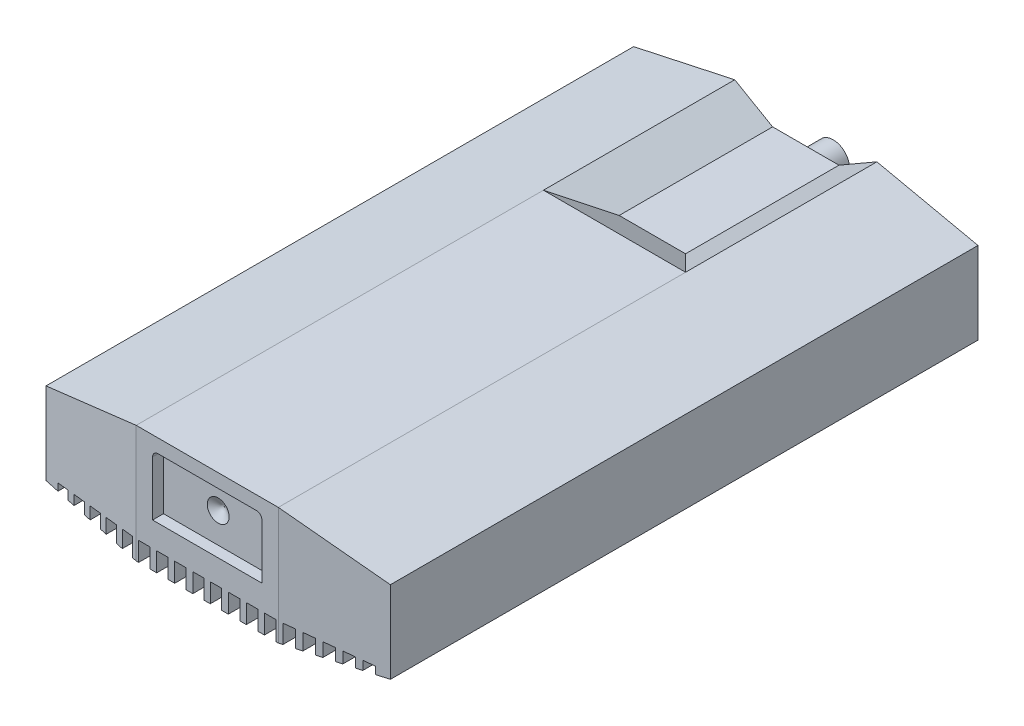
SolidWorks part; units mm, degrees
ref_plane "前视基准面" through (0, 0, 0) normal (0, 0, 1) x (1, 0, 0)
ref_plane "上视基准面" through (0, 0, 0) normal (0, 1, 0) x (1, 0, 0)
ref_plane "右视基准面" through (0, 0, 0) normal (1, 0, 0) x (0, 0, -1)
sketch "草图1" plane through (0, 0, 0) normal (0, 0, 1) x (1, 0, 0)
  line L0 (-31.5, 0) -> (31.5, 0) construction
  line L1 (0, 10.75) -> (0, -10.75) construction
  line L2 (31.5, 6.75) -> (31.5, -8.25)
  line L3 (-13, 10.75) -> (13, 10.75)
  line L4 (13, 10.75) -> (31.5, 6.75)
  line L5 (-13, -10.75) -> (-12.55, -10.75)
  line L6 (13, -10.75) -> (13.75, -10.6486)
  line L7 (-13, 10.75) -> (-31.5, 6.75)
  line L8 (-13, -10.75) -> (-13.75, -10.6486)
  line L9 (-31.5, 6.75) -> (-31.5, -8.25)
  line L10 (-31.5, -7.25) -> (31.5, -7.25) construction
  line L11 (-0.55, -7.25) -> (-0.55, -10.75)
  line L12 (0.55, -7.25) -> (0.55, -10.75)
  line L13 (2.65, -7.25) -> (2.65, -10.75)
  line L14 (-2.65, -7.25) -> (-2.65, -10.75)
  line L15 (-2.65, -7.25) -> (-0.55, -7.25)
  line L16 (0.55, -7.25) -> (2.65, -7.25)
  line L17 (3.85, -7.25) -> (3.85, -10.75)
  line L18 (3.85, -7.25) -> (5.95, -7.25)
  line L19 (5.95, -7.25) -> (5.95, -10.75)
  line L20 (7.15, -7.25) -> (7.15, -10.75)
  line L21 (7.15, -7.25) -> (9.25, -7.25)
  line L22 (9.25, -7.25) -> (9.25, -10.75)
  line L23 (10.45, -7.25) -> (10.45, -10.75)
  line L24 (10.45, -7.25) -> (12.55, -7.25)
  line L25 (12.55, -7.25) -> (12.55, -10.75)
  line L26 (13.75, -7.25) -> (13.75, -10.6486)
  line L27 (13.75, -7.25) -> (15.85, -7.25)
  line L28 (15.85, -7.25) -> (15.85, -10.3649)
  line L29 (17.05, -7.25) -> (17.05, -10.2027)
  line L30 (17.05, -7.25) -> (19.15, -7.25)
  line L31 (19.15, -7.25) -> (19.15, -9.9189)
  line L32 (20.35, -7.25) -> (20.35, -9.7568)
  line L33 (20.35, -7.25) -> (22.45, -7.25)
  line L34 (22.45, -7.25) -> (22.45, -9.473)
  line L35 (23.65, -7.25) -> (23.65, -9.3108)
  line L36 (23.65, -7.25) -> (25.75, -7.25)
  line L37 (25.75, -7.25) -> (25.75, -9.027)
  line L38 (26.95, -7.25) -> (26.95, -8.8649)
  line L39 (26.95, -7.25) -> (29.05, -7.25)
  line L40 (29.05, -7.25) -> (29.05, -8.5811)
  line L41 (-5.95, -7.25) -> (-5.95, -10.75)
  line L42 (-5.95, -7.25) -> (-3.85, -7.25)
  line L43 (-3.85, -7.25) -> (-3.85, -10.75)
  line L44 (-9.25, -7.25) -> (-9.25, -10.75)
  line L45 (-9.25, -7.25) -> (-7.15, -7.25)
  line L46 (-7.15, -7.25) -> (-7.15, -10.75)
  line L47 (-12.55, -7.25) -> (-12.55, -10.75)
  line L48 (-12.55, -7.25) -> (-10.45, -7.25)
  line L49 (-10.45, -7.25) -> (-10.45, -10.75)
  line L50 (-15.85, -7.25) -> (-15.85, -10.3649)
  line L51 (-15.85, -7.25) -> (-13.75, -7.25)
  line L52 (-13.75, -7.25) -> (-13.75, -10.6486)
  line L53 (-19.15, -7.25) -> (-19.15, -9.9189)
  line L54 (-19.15, -7.25) -> (-17.05, -7.25)
  line L55 (-17.05, -7.25) -> (-17.05, -10.2027)
  line L56 (-22.45, -7.25) -> (-22.45, -9.473)
  line L57 (-22.45, -7.25) -> (-20.35, -7.25)
  line L58 (-20.35, -7.25) -> (-20.35, -9.7568)
  line L59 (-25.75, -7.25) -> (-25.75, -9.027)
  line L60 (-25.75, -7.25) -> (-23.65, -7.25)
  line L61 (-23.65, -7.25) -> (-23.65, -9.3108)
  line L62 (-29.05, -7.25) -> (-29.05, -8.5811)
  line L63 (-29.05, -7.25) -> (-26.95, -7.25)
  line L64 (-26.95, -7.25) -> (-26.95, -8.8649)
  line L65 (29.05, -8.5811) -> (31.5, -8.25)
  line L66 (25.75, -9.027) -> (26.95, -8.8649)
  line L67 (22.45, -9.473) -> (23.65, -9.3108)
  line L68 (19.15, -9.9189) -> (20.35, -9.7568)
  line L69 (15.85, -10.3649) -> (17.05, -10.2027)
  line L70 (12.55, -10.75) -> (13, -10.75)
  line L71 (9.25, -10.75) -> (10.45, -10.75)
  line L72 (5.95, -10.75) -> (7.15, -10.75)
  line L73 (2.65, -10.75) -> (3.85, -10.75)
  line L74 (-0.55, -10.75) -> (0.55, -10.75)
  line L75 (-3.85, -10.75) -> (-2.65, -10.75)
  line L76 (-7.15, -10.75) -> (-5.95, -10.75)
  line L77 (-10.45, -10.75) -> (-9.25, -10.75)
  line L78 (-15.85, -10.3649) -> (-17.05, -10.2027)
  line L79 (-19.15, -9.9189) -> (-20.35, -9.7568)
  line L80 (-22.45, -9.473) -> (-23.65, -9.3108)
  line L81 (-25.75, -9.027) -> (-26.95, -8.8649)
  line L82 (-29.05, -8.5811) -> (-31.5, -8.25)
  point P5 (0, 0)
  point P6 (0, 0)
  dimension "D1" = 63
  dimension "D2" = 21.5
  dimension "D3" = 15
  dimension "D4" = 4
  dimension "D5" = 13
  dimension "D6" = 1
  dimension "D7" = 1.1
  dimension "D8" = 2.1
  dimension "D9" = 2.1
  dimension "D10" = 9
  dimension "D11" = 9
extrude "凸台-拉伸1" add sketch "草图1" along normal blind 109.5
sketch "草图2" plane through (0, 10.75, 0) normal (0, 1, 0) x (1, 0, 0)
  line L0 (13, -109.5) -> (13, 0) construction
  line L1 (-13, 15) -> (13, 15)
  line L2 (-13, 15) -> (-13, -35)
  line L3 (-13, -35) -> (13, -35)
  line L4 (13, 15) -> (13, -35)
  line L5 (13, 0) -> (-13, 0) construction
  line L6 (-13, -109.5) -> (-13, 0) construction
  dimension "D1" = 35
  dimension "D2" = 50
extrude "切除-拉伸1" cut sketch "草图2" against normal up to vertex (4 mm away) draft 60 up to point (31.5, 6.75, 0)
sketch "草图3" plane through (31.5, 0, 0) normal (1, 0, 0) x (0, 0, -1)
  line L0 (0, -8.25) -> (-2.5, -10.75)
  line L1 (-109.5, -10.75) -> (0, -10.75) construction
  line L2 (-2.5, -10.75) -> (0, -10.75)
  line L3 (0, -10.75) -> (0, -8.25)
extrude "切除-拉伸2" cut sketch "草图3" against normal through all
sketch "草图4" plane through (0, 10.75, 0) normal (0, 1, 0) x (1, 0, 0)
  line L0 (13, -109.5) -> (31.5, -107.5)
  line L1 (31.5, -107.5) -> (31.5, -109.5)
  line L2 (31.5, -109.5) -> (13, -109.5)
  line L3 (-31.5, -107.5) -> (-31.5, -109.5)
  line L4 (-31.5, -109.5) -> (-31.5, 0) construction
  line L5 (-31.5, -109.5) -> (-13, -109.5)
  line L6 (-13, -109.5) -> (-31.5, -107.5)
  dimension "D1" = 2
extrude "切除-拉伸3" cut sketch "草图4" against normal through all
sketch "草图5" plane through (0, 0, 109.5) normal (0, 0, 1) x (1, 0, 0)
  line L1 (-9, 8.25) -> (9, 8.25)
  line L2 (-10, 7.25) -> (-10, -2.75)
  line L3 (-10, -2.75) -> (10, -2.75)
  line L4 (10, 7.25) -> (10, -2.75)
  arc A0 (-9, 8.25) -> (-10, 7.25) centre (-9, 7.25) ccw
  arc A1 (9, 8.25) -> (10, 7.25) centre (9, 7.25) cw
  point P4 (0, 8.25)
  point P9 (-10, 8.25)
  point P12 (10, 8.25)
  dimension "D4" = 1
  dimension "D1" = 5.5
  dimension "D2" = 11
  dimension "D3" = 20
extrude "切除-拉伸4" cut sketch "草图5" against normal blind 2
sketch "草图6" plane through (0, 0, 107.5) normal (0, 0, 1) x (1, 0, 0)
  line L0 (9, 8.25) -> (-9, 8.25) construction
  line L1 (9, 8.25) -> (-9, 8.25) construction
  circle A0 centre (0, 2.75) radius 2
  point P4 (0, 8.25)
  dimension "D1" = 5.5
  dimension "D2" = 4
extrude "切除-拉伸5" cut sketch "草图6" against normal blind 2 draft 60
sketch "草图7" plane through (0, -10.75, 0) normal (0, -1, 0) x (1, 0, 0)
  line L0 (0, 0) -> (0, 109.5) construction
  line L1 (-0.55, 109.5) -> (0.55, 109.5) construction
  line L2 (3.85, 0) -> (5.95, 0) construction
  line L3 (-7, 84.5) -> (7, 84.5) construction
  line L4 (-7, 84.5) -> (-7, 4.5) construction
  line L5 (-7, 4.5) -> (7, 4.5) construction
  line L6 (7, 84.5) -> (7, 4.5) construction
  line L8 (-10.4, 82.5) -> (-3.6, 82.5)
  line L9 (-10.4, 82.5) -> (-10.4, 86.5)
  line L10 (-10.4, 86.5) -> (-3.6, 86.5)
  line L11 (-3.6, 82.5) -> (-3.6, 86.5)
  line L12 (-10.4, 82.5) -> (-3.6, 86.5) construction
  line L13 (-10.4, 86.5) -> (-3.6, 82.5) construction
  line L14 (3.6, 82.5) -> (10.4, 82.5)
  line L15 (3.6, 82.5) -> (3.6, 86.5)
  line L16 (3.6, 86.5) -> (10.4, 86.5)
  line L17 (10.4, 82.5) -> (10.4, 86.5)
  line L18 (3.6, 82.5) -> (10.4, 86.5) construction
  line L19 (3.6, 86.5) -> (10.4, 82.5) construction
  line L20 (3.6, 2.5) -> (10.4, 2.5)
  line L21 (3.6, 2.5) -> (3.6, 6.5)
  line L22 (3.6, 6.5) -> (10.4, 6.5)
  line L23 (10.4, 2.5) -> (10.4, 6.5)
  line L24 (3.6, 2.5) -> (10.4, 6.5) construction
  line L25 (3.6, 6.5) -> (10.4, 2.5) construction
  line L26 (-10.4, 2.5) -> (-3.6, 2.5)
  line L27 (-10.4, 2.5) -> (-10.4, 6.5)
  line L28 (-10.4, 6.5) -> (-3.6, 6.5)
  line L29 (-3.6, 2.5) -> (-3.6, 6.5)
  line L30 (-10.4, 2.5) -> (-3.6, 6.5) construction
  line L31 (-10.4, 6.5) -> (-3.6, 2.5) construction
  point P9 (0, 4.5)
  dimension "D1" = 14
  dimension "D2" = 80
  dimension "D3" = 4.5
  dimension "D4" = 4
  dimension "D5" = 6.8
extrude "凸台-拉伸2" add sketch "草图7" against normal up to surface (3.5 mm away) up to face at (1.6, -7.25, 54.75)
hole_wizard "M2 螺纹孔1" positions "草图9" profile "草图10" tap size "M2" standard "GB"
sketch "草图9" plane through (0, -10.75, 0) normal (0, -1, 0) x (-1, 0, 0)
  line L1 (7, -84.5) -> (-7, -84.5) construction
  line L2 (7, -84.5) -> (7, -4.5) construction
  line L3 (7, -4.5) -> (-7, -4.5) construction
  line L4 (-7, -84.5) -> (-7, -4.5) construction
  point P0 (7, -4.5)
  point P2 (-7, -4.5)
  point P4 (7, -84.5)
  point P6 (-7, -84.5)
  point P81 (0, -4.5)
  dimension "D1" = 4.5
  dimension "D2" = 14
  dimension "D3" = 80
sketch "草图10" plane through (-7, -10.75, 4.5) normal (1, 0, 0) x (0, 0, -1)
  line L0 (0, 0) -> (0, 5.6807)
  line L1 (0, 5.6807) -> (0.8, 5.2)
  line L2 (0.8, 5.2) -> (0.8, 0)
  line L5 (0.8, 0) -> (0, 0)
  line L10 (0, 5.6807) -> (-0.8, 5.2) construction
  line L11 (0, -6.35) -> (0, 107.95) construction
  dimension "螺纹孔钻头直径" = 1.6
  dimension "螺纹孔钻头深度" = 5.2
  dimension "导头角度" = 118
cosmetic thread "孔螺蚊线1" parameters "D1"=4, "D2"=2
cosmetic thread "孔螺蚊线2" parameters "D1"=4, "D2"=2
cosmetic thread "孔螺蚊线3" parameters "D1"=4, "D2"=2
cosmetic thread "孔螺蚊线4" parameters "D1"=4, "D2"=2
sketch "草图11" plane through (0, 0, 0) normal (0, 0, -1) x (-1, 0, 0)
  line L0 (10, -2.75) -> (-10, -2.75) construction
  line L1 (0, 0) -> (0, 6.75) construction
  line L2 (6.0718, 6.75) -> (-6.0718, 6.75) construction
  circle A0 centre (5, -2.75) radius 3
  circle A1 centre (-5, -2.75) radius 3
  dimension "D1" = 10
  dimension "D2" = 6
extrude "凸台-拉伸3" add sketch "草图11" along normal blind 10
